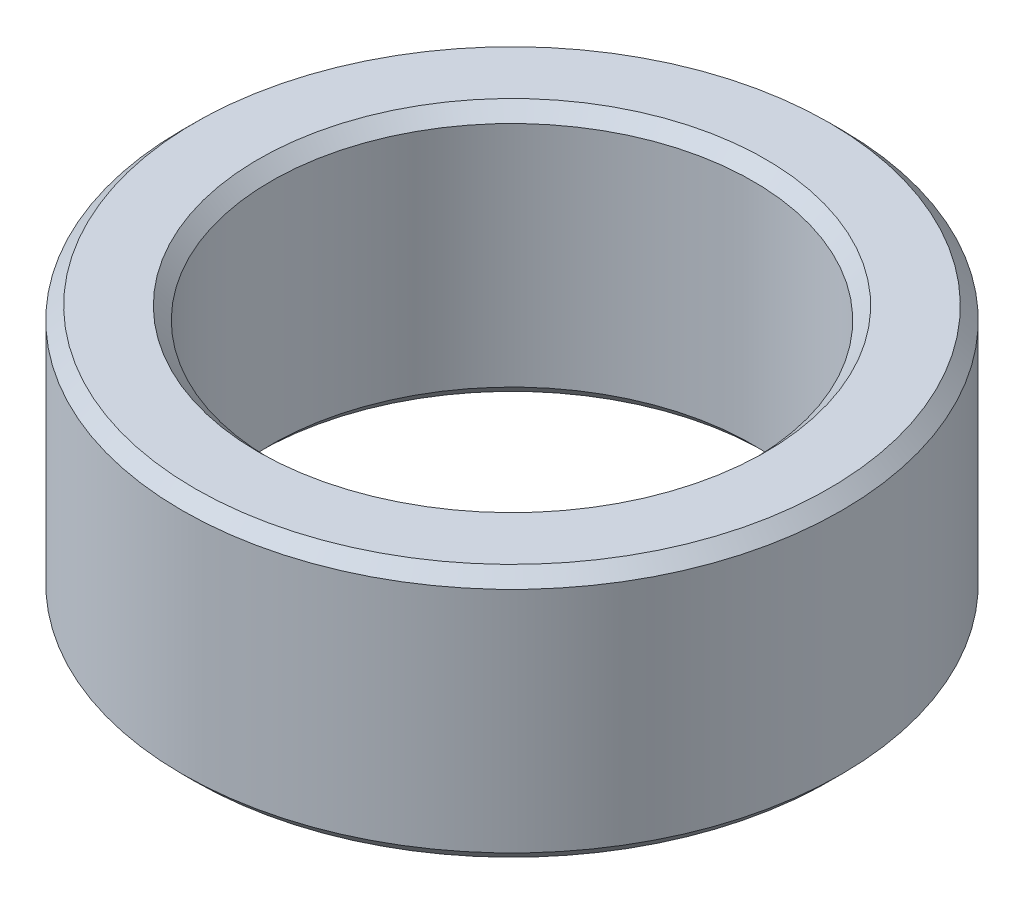
SolidWorks part; units mm, degrees
ref_plane "Front Plane" through (0, 0, 0) normal (0, 0, 1) x (1, 0, 0)
ref_plane "Top Plane" through (0, 0, 0) normal (0, 1, 0) x (1, 0, 0)
ref_plane "Right Plane" through (0, 0, 0) normal (1, 0, 0) x (0, 0, -1)
sketch "Sketch1" plane through (0, 0, 0) normal (0, 1, 0) x (1, 0, 0)
  circle A0 centre (0, 0) radius 4.75
  circle A1 centre (0, 0) radius 6.5
  dimension "D1" = 13
  dimension "D2" = 9.5
extrude "Boss-Extrude1" add sketch "Sketch1" along normal blind 5
chamfer "Chamfer1" distance 0.25 angle 45 4 edges at (0, 0, 4.75) (0, 0, 6.5) (0, 5, 4.75) (0, 5, 6.5)
